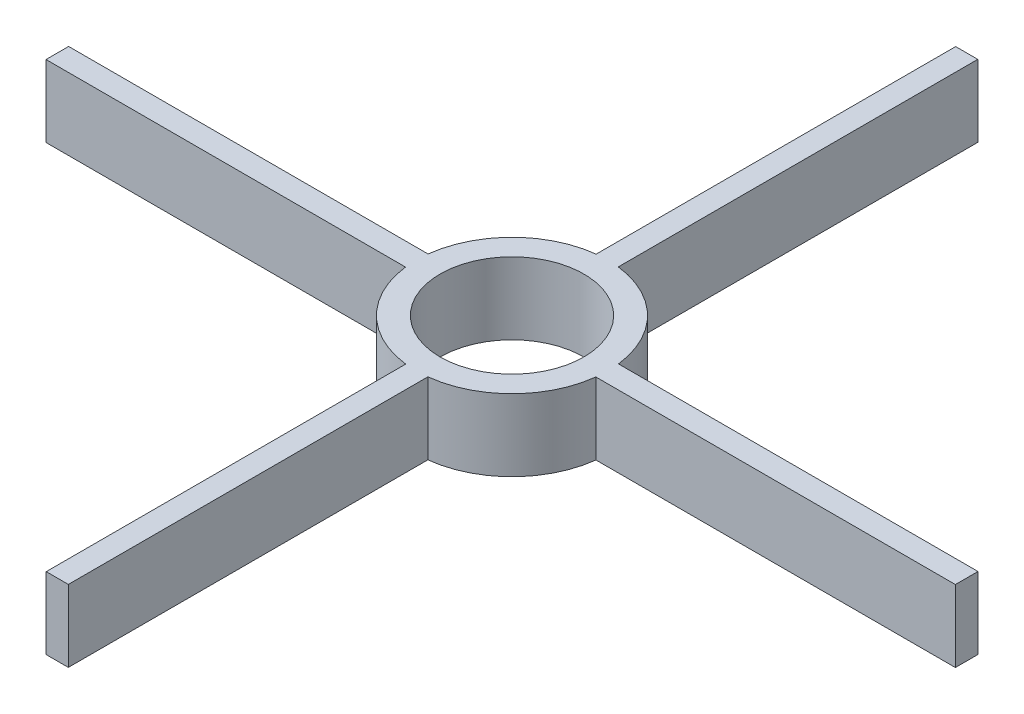
SolidWorks part; units mm, degrees
material "A286 Iron Base Superalloy"
ref_plane "Front Plane" through (0, 0, 0) normal (0, 0, 1) x (1, 0, 0)
ref_plane "Top Plane" through (0, 0, 0) normal (0, 1, 0) x (1, 0, 0)
ref_plane "Right Plane" through (0, 0, 0) normal (1, 0, 0) x (0, 0, -1)
sketch "Sketch1" plane through (0, 0, 0) normal (0, 1, 0) x (1, 0, 0)
  line L0 (0, 94.6678) -> (0, -121.0063) construction
  line L1 (-4.6149, 39.7329) -> (-4.6149, 189.7329)
  line L2 (4.6149, 39.7329) -> (4.6149, 189.7329)
  line L3 (4.6149, -189.7329) -> (-4.6149, -189.7329)
  line L4 (4.6149, -189.7329) -> (4.6149, -39.7329)
  line L5 (4.6149, 189.7329) -> (-4.6149, 189.7329)
  line L7 (-4.6149, -189.7329) -> (-4.6149, -39.7329)
  line L8 (-189.7205, -4.7202) -> (-189.7205, 4.7202)
  line L9 (189.7205, -4.7202) -> (39.7205, -4.7202)
  line L10 (189.7205, -4.7202) -> (189.7205, 4.7202)
  line L11 (189.7205, 4.7202) -> (39.7205, 4.7202)
  line L13 (-189.7205, -4.7202) -> (-39.7205, -4.7202)
  line L14 (-189.7205, 4.7202) -> (-39.7205, 4.7202)
  circle A0 centre (0, 0) radius 30
  arc A2 (4.6149, -39.7329) -> (39.7205, -4.7202) centre (0, 0) ccw
  arc A4 (39.7205, 4.7202) -> (4.6149, 39.7329) centre (0, 0) ccw
  arc A5 (-39.7205, 4.7202) -> (-4.6149, 39.7329) centre (0, 0) cw
  arc A6 (-4.6149, -39.7329) -> (-39.7205, -4.7202) centre (0, 0) cw
  point P5 (0, 0)
  point P10 (0, 0)
  point P16 (0, 189.7329)
  point P19 (0, -189.7329)
  dimension "D4" = 60
  dimension "D1" = 150
  dimension "D2" = 150
  dimension "D6" = 150
extrude "Boss-Extrude2" add sketch "Sketch1" along normal mid plane 30
